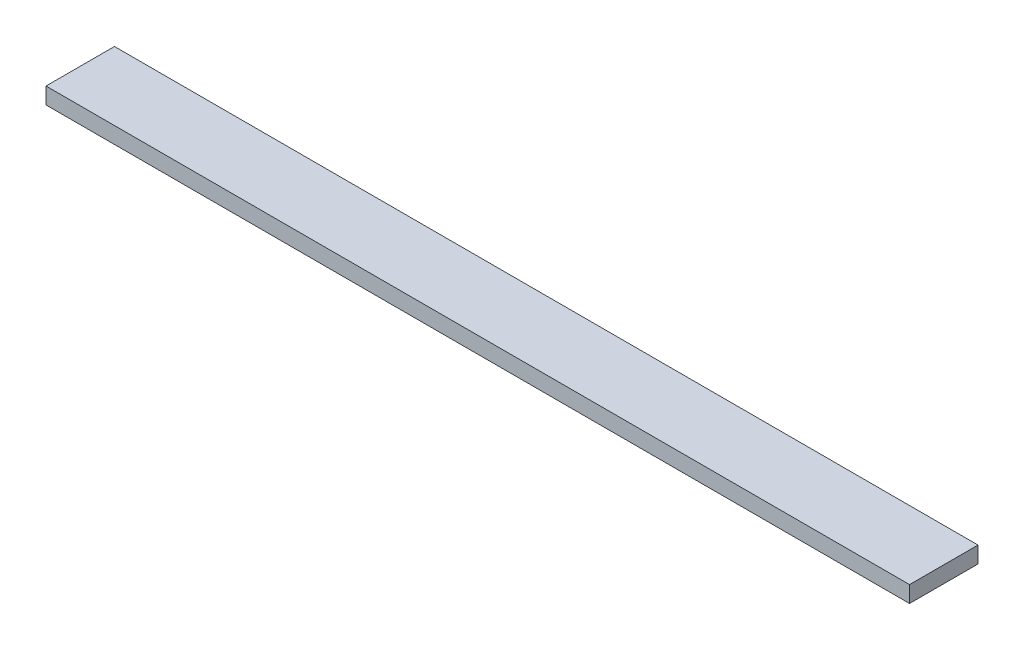
SolidWorks part; units mm, degrees
material "Plywood"
ref_plane "Front Plane" through (0, 0, 0) normal (0, 0, 1) x (1, 0, 0)
ref_plane "Top Plane" through (0, 0, 0) normal (0, 1, 0) x (1, 0, 0)
ref_plane "Right Plane" through (0, 0, 0) normal (1, 0, 0) x (0, 0, -1)
sketch "Sketch1" plane through (0, 0, 0) normal (0, 1, 0) x (1, 0, 0)
  line L1 (-480.568, -38.1) -> (480.568, -38.1)
  line L2 (-480.568, -38.1) -> (-480.568, 38.1)
  line L3 (-480.568, 38.1) -> (480.568, 38.1)
  line L4 (480.568, -38.1) -> (480.568, 38.1)
  line L5 (-480.568, -38.1) -> (480.568, 38.1) construction
  line L6 (-480.568, 38.1) -> (480.568, -38.1) construction
  point P0 (0, 0)
  dimension "D1" = 961.136
  dimension "D2" = 76.2
extrude "Boss-Extrude1" add sketch "Sketch1" along normal blind 18.2562
